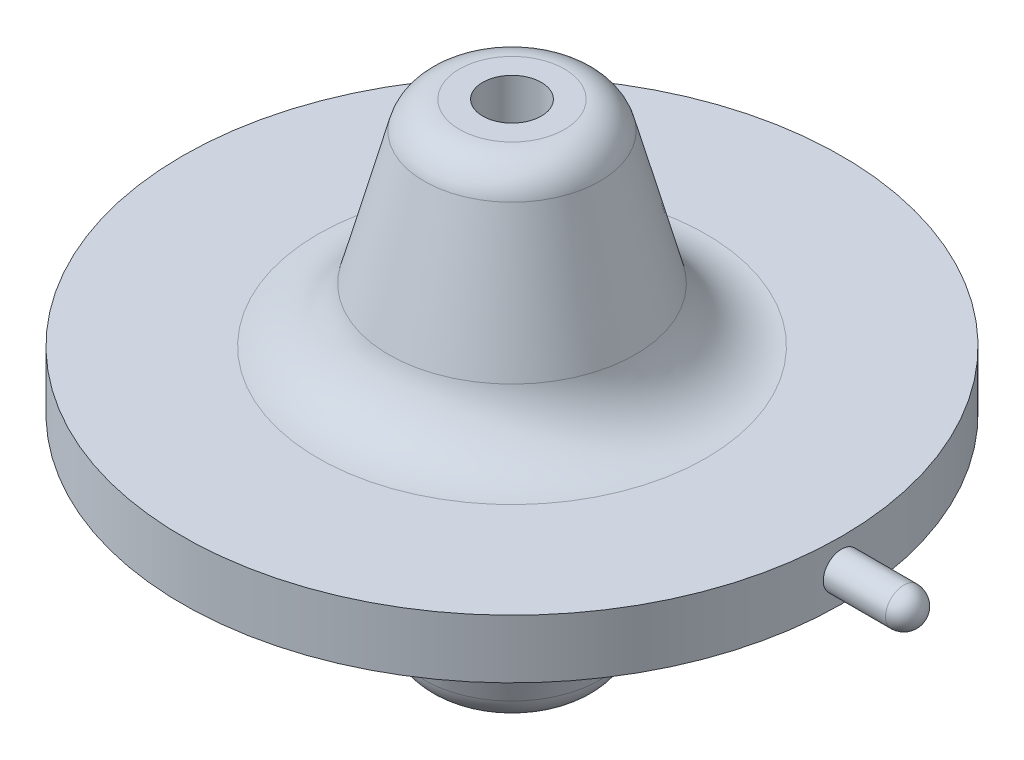
SolidWorks part; units mm, degrees
ref_plane "Front Plane" through (0, 0, 0) normal (0, 0, 1) x (1, 0, 0)
ref_plane "Top Plane" through (0, 0, 0) normal (0, 1, 0) x (1, 0, 0)
ref_plane "Right Plane" through (0, 0, 0) normal (1, 0, 0) x (0, 0, -1)
sketch "Sketch1" plane through (0, 0, 0) normal (0, 0, 1) x (1, 0, 0)
  line L0 (0, 35.9799) -> (0, -45.2253) construction
  line L1 (-45, 0) -> (74.7335, 0) construction
  line L2 (0, 33.2) -> (-7.1634, 33.2)
  line L3 (-11.993, 29.4941) -> (-16.8381, 11.4118)
  line L4 (-26.4974, 4) -> (-45, 4)
  line L5 (-45, 4) -> (-45, -4)
  line L6 (-26.4974, -4) -> (-45, -4)
  line L7 (-11.993, -29.4941) -> (-16.8381, -11.4118)
  line L8 (0, -33.2) -> (-7.1634, -33.2)
  line L9 (0, 33.2) -> (0, -33.2)
  arc A0 (-16.8381, 11.4118) -> (-26.4974, 4) centre (-26.4974, 14) cw
  arc A1 (-7.1634, 33.2) -> (-11.993, 29.4941) centre (-7.1634, 28.2) ccw
  arc A2 (-7.1634, -33.2) -> (-11.993, -29.4941) centre (-7.1634, -28.2) cw
  arc A3 (-16.8381, -11.4118) -> (-26.4974, -4) centre (-26.4974, -14) ccw
  point P13 (-11, 33.2)
  point P22 (-11, -33.2)
  dimension "D6" = 10
  dimension "D7" = 5
  dimension "D1" = 33.2
  dimension "D2" = 11
  dimension "D3" = 105
  dimension "D4" = 45
  dimension "D5" = 4
revolve "Revolve1" add sketch "Sketch1" angle 360 about L9
sketch "Sketch2" plane through (0, 33.2, 0) normal (0, 1, 0) x (1, 0, 0)
  circle A0 centre (0, 0) radius 4
  dimension "D1" = 8
extrude "Cut-Extrude1" cut sketch "Sketch2" against normal through all
sketch "Sketch3" plane through (0, 0, 0) normal (0, 0, 1) x (1, 0, 0)
  line L0 (0, 0) -> (53.5, 0) construction
  line L1 (53.5, 2.5) -> (45, 2.5)
  line L2 (45, -4) -> (45, 4) construction
  line L3 (45, 0) -> (56, 0)
  line L4 (45, 0) -> (45, 2.5)
  arc A1 (56, 0) -> (53.5, 2.5) centre (53.5, 0) ccw
  dimension "D1" = 2.5
  dimension "D2" = 11
revolve "Revolve2" add sketch "Sketch3" angle 360 about L0
